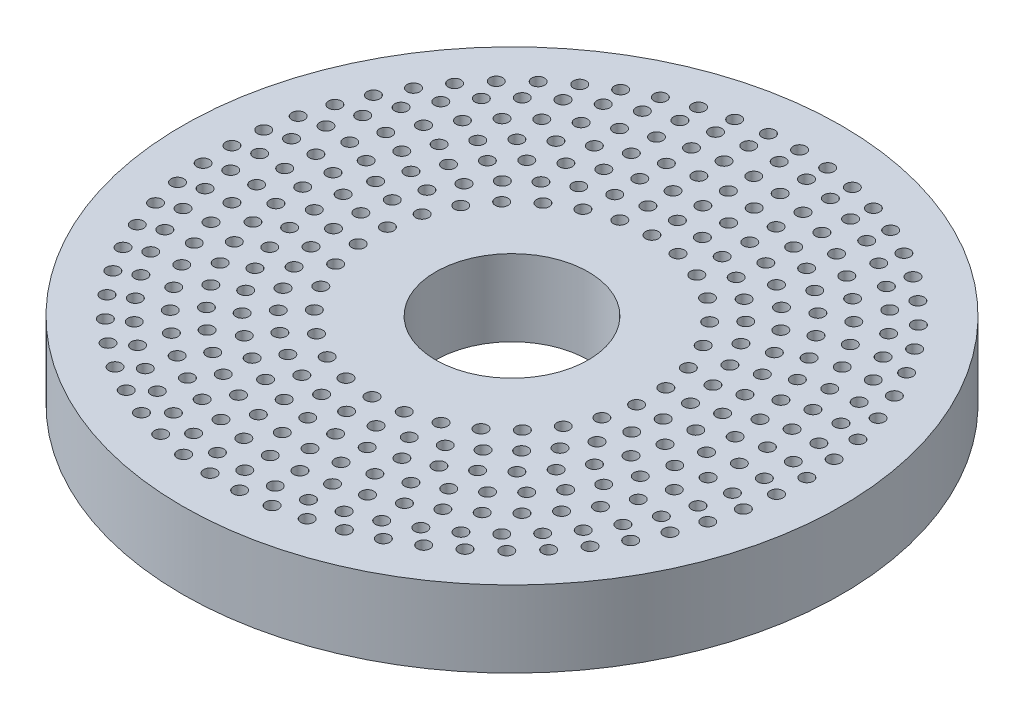
SolidWorks part; units mm, degrees
ref_plane "Ön Düzlem" through (0, 0, 0) normal (0, 0, 1) x (1, 0, 0)
ref_plane "Üst Düzlem" through (0, 0, 0) normal (0, 1, 0) x (1, 0, 0)
ref_plane "Sağ Düzlem" through (0, 0, 0) normal (1, 0, 0) x (0, 0, -1)
sketch "Çizim1" plane through (0, 0, 0) normal (0, 1, 0) x (1, 0, 0)
  line L0 (0, 0) -> (0, 55)
  line L1 (0, 55) -> (0, 65)
  line L2 (0, 65) -> (0, 75)
  line L3 (0, 75) -> (0, 85)
  line L4 (0, 85) -> (0, 95)
  line L5 (0, 95) -> (0, 105)
  line L6 (0, 105) -> (0, 113)
  circle A0 centre (0, 0) radius 129.5
  circle A1 centre (0, 55) radius 2.5
  circle A2 centre (0, 65) radius 2.5
  circle A3 centre (0, 75) radius 2.5
  circle A4 centre (0, 85) radius 2.5
  circle A5 centre (0, 95) radius 2.5
  circle A6 centre (0, 105) radius 2.5
  circle A7 centre (0, 113) radius 2.5
  circle A8 centre (11.4351, 53.7981) radius 2.5
  circle A9 centre (22.3705, 50.245) radius 2.5
  circle A10 centre (32.3282, 44.4959) radius 2.5
  circle A11 centre (40.873, 36.8022) radius 2.5
  circle A12 centre (47.6314, 27.5) radius 2.5
  circle A13 centre (52.3081, 16.9959) radius 2.5
  circle A14 centre (54.6987, 5.7491) radius 2.5
  circle A15 centre (54.6987, -5.7491) radius 2.5
  circle A16 centre (52.3081, -16.9959) radius 2.5
  circle A17 centre (47.6314, -27.5) radius 2.5
  circle A18 centre (40.873, -36.8022) radius 2.5
  circle A19 centre (32.3282, -44.4959) radius 2.5
  circle A20 centre (22.3705, -50.245) radius 2.5
  circle A21 centre (11.4351, -53.7981) radius 2.5
  circle A22 centre (0, -55) radius 2.5
  circle A23 centre (-11.4351, -53.7981) radius 2.5
  circle A24 centre (-22.3705, -50.245) radius 2.5
  circle A25 centre (-32.3282, -44.4959) radius 2.5
  circle A26 centre (-40.873, -36.8022) radius 2.5
  circle A27 centre (-47.6314, -27.5) radius 2.5
  circle A28 centre (-52.3081, -16.9959) radius 2.5
  circle A29 centre (-54.6987, -5.7491) radius 2.5
  circle A30 centre (-54.6987, 5.7491) radius 2.5
  circle A31 centre (-52.3081, 16.9959) radius 2.5
  circle A32 centre (-47.6314, 27.5) radius 2.5
  circle A33 centre (-40.873, 36.8022) radius 2.5
  circle A34 centre (-32.3282, 44.4959) radius 2.5
  circle A35 centre (-22.3705, 50.245) radius 2.5
  circle A36 centre (-11.4351, 53.7981) radius 2.5
  circle A37 centre (10.6986, 64.1135) radius 2.5
  circle A38 centre (21.1055, 61.4781) radius 2.5
  circle A39 centre (30.9366, 57.1658) radius 2.5
  circle A40 centre (39.9238, 51.2941) radius 2.5
  circle A41 centre (47.8221, 44.0233) radius 2.5
  circle A42 centre (54.4158, 35.5516) radius 2.5
  circle A43 centre (59.5253, 26.1102) radius 2.5
  circle A44 centre (63.011, 15.9566) radius 2.5
  circle A45 centre (64.778, 5.3677) radius 2.5
  circle A46 centre (64.778, -5.3677) radius 2.5
  circle A47 centre (63.011, -15.9566) radius 2.5
  circle A48 centre (59.5253, -26.1102) radius 2.5
  circle A49 centre (54.4158, -35.5516) radius 2.5
  circle A50 centre (47.8221, -44.0233) radius 2.5
  circle A51 centre (39.9238, -51.2941) radius 2.5
  circle A52 centre (30.9366, -57.1658) radius 2.5
  circle A53 centre (21.1055, -61.4781) radius 2.5
  circle A54 centre (10.6986, -64.1135) radius 2.5
  circle A55 centre (0, -65) radius 2.5
  circle A56 centre (-10.6986, -64.1135) radius 2.5
  circle A57 centre (-21.1055, -61.4781) radius 2.5
  circle A58 centre (-30.9366, -57.1658) radius 2.5
  circle A59 centre (-39.9238, -51.2941) radius 2.5
  circle A60 centre (-47.8221, -44.0233) radius 2.5
  circle A61 centre (-54.4158, -35.5516) radius 2.5
  circle A62 centre (-59.5253, -26.1102) radius 2.5
  circle A63 centre (-63.011, -15.9566) radius 2.5
  circle A64 centre (-64.778, -5.3677) radius 2.5
  circle A65 centre (-64.778, 5.3677) radius 2.5
  circle A66 centre (-63.011, 15.9566) radius 2.5
  circle A67 centre (-59.5253, 26.1102) radius 2.5
  circle A68 centre (-54.4158, 35.5516) radius 2.5
  circle A69 centre (-47.8221, 44.0233) radius 2.5
  circle A70 centre (-39.9238, 51.2941) radius 2.5
  circle A71 centre (-30.9366, 57.1658) radius 2.5
  circle A72 centre (-21.1055, 61.4781) radius 2.5
  circle A73 centre (-10.6986, 64.1135) radius 2.5
  circle A74 centre (10.9201, 74.2008) radius 2.5
  circle A75 centre (21.6074, 71.82) radius 2.5
  circle A76 centre (31.8343, 67.9086) radius 2.5
  circle A77 centre (41.3826, 62.5498) radius 2.5
  circle A78 centre (50.0489, 55.8579) radius 2.5
  circle A79 centre (57.6485, 47.9755) radius 2.5
  circle A80 centre (64.0195, 39.0705) radius 2.5
  circle A81 centre (69.026, 29.3329) radius 2.5
  circle A82 centre (72.5613, 18.97) radius 2.5
  circle A83 centre (74.5501, 8.2028) radius 2.5
  circle A84 centre (74.95, -2.7392) radius 2.5
  circle A85 centre (73.7524, -13.6228) radius 2.5
  circle A86 centre (70.983, -24.216) radius 2.5
  circle A87 centre (66.7007, -34.2932) radius 2.5
  circle A88 centre (60.9967, -43.6394) radius 2.5
  circle A89 centre (53.9928, -52.0556) radius 2.5
  circle A90 centre (45.838, -59.3622) radius 2.5
  circle A91 centre (36.7063, -65.4037) radius 2.5
  circle A92 centre (26.7923, -70.0512) radius 2.5
  circle A93 centre (16.3073, -73.2057) radius 2.5
  circle A94 centre (5.4746, -74.7999) radius 2.5
  circle A95 centre (-5.4746, -74.7999) radius 2.5
  circle A96 centre (-16.3073, -73.2057) radius 2.5
  circle A97 centre (-26.7923, -70.0512) radius 2.5
  circle A98 centre (-36.7063, -65.4037) radius 2.5
  circle A99 centre (-45.838, -59.3622) radius 2.5
  circle A100 centre (-53.9928, -52.0556) radius 2.5
  circle A101 centre (-60.9967, -43.6394) radius 2.5
  circle A102 centre (-66.7007, -34.2932) radius 2.5
  circle A103 centre (-70.983, -24.216) radius 2.5
  circle A104 centre (-73.7524, -13.6228) radius 2.5
  circle A105 centre (-74.95, -2.7392) radius 2.5
  circle A106 centre (-74.5501, 8.2028) radius 2.5
  circle A107 centre (-72.5613, 18.97) radius 2.5
  circle A108 centre (-69.026, 29.3329) radius 2.5
  circle A109 centre (-64.0195, 39.0705) radius 2.5
  circle A110 centre (-57.6485, 47.9755) radius 2.5
  circle A111 centre (-50.0489, 55.8579) radius 2.5
  circle A112 centre (-41.3826, 62.5498) radius 2.5
  circle A113 centre (-31.8343, 67.9086) radius 2.5
  circle A114 centre (-21.6074, 71.82) radius 2.5
  circle A115 centre (-10.9201, 74.2008) radius 2.5
  circle A116 centre (10.8696, 84.3022) radius 2.5
  circle A117 centre (21.5606, 82.2201) radius 2.5
  circle A118 centre (31.8977, 78.7879) radius 2.5
  circle A119 centre (41.711, 74.0621) radius 2.5
  circle A120 centre (50.8394, 68.1202) radius 2.5
  circle A121 centre (59.133, 61.0597) radius 2.5
  circle A122 centre (66.4557, 52.9966) radius 2.5
  circle A123 centre (72.6871, 44.0634) radius 2.5
  circle A124 centre (77.7251, 34.4066) radius 2.5
  circle A125 centre (81.4868, 24.1848) radius 2.5
  circle A126 centre (83.9105, 13.566) radius 2.5
  circle A127 centre (84.9563, 2.7244) radius 2.5
  circle A128 centre (84.6072, -8.162) radius 2.5
  circle A129 centre (82.8689, -18.9143) radius 2.5
  circle A130 centre (79.7698, -29.356) radius 2.5
  circle A131 centre (75.3609, -39.3158) radius 2.5
  circle A132 centre (69.7146, -48.6299) radius 2.5
  circle A133 centre (62.9236, -57.1456) radius 2.5
  circle A134 centre (55.0994, -64.7229) radius 2.5
  circle A135 centre (46.3705, -71.2375) radius 2.5
  circle A136 centre (36.8801, -76.5824) radius 2.5
  circle A137 centre (26.7842, -80.6697) radius 2.5
  circle A138 centre (16.2485, -83.4325) radius 2.5
  circle A139 centre (5.446, -84.8254) radius 2.5
  circle A140 centre (-5.446, -84.8254) radius 2.5
  circle A141 centre (-16.2485, -83.4325) radius 2.5
  circle A142 centre (-26.7842, -80.6697) radius 2.5
  circle A143 centre (-36.8801, -76.5824) radius 2.5
  circle A144 centre (-46.3705, -71.2375) radius 2.5
  circle A145 centre (-55.0994, -64.7229) radius 2.5
  circle A146 centre (-62.9236, -57.1456) radius 2.5
  circle A147 centre (-69.7146, -48.6299) radius 2.5
  circle A148 centre (-75.3609, -39.3158) radius 2.5
  circle A149 centre (-79.7698, -29.356) radius 2.5
  circle A150 centre (-82.8689, -18.9143) radius 2.5
  circle A151 centre (-84.6072, -8.162) radius 2.5
  circle A152 centre (-84.9563, 2.7244) radius 2.5
  circle A153 centre (-83.9105, 13.566) radius 2.5
  circle A154 centre (-81.4868, 24.1848) radius 2.5
  circle A155 centre (-77.7251, 34.4066) radius 2.5
  circle A156 centre (-72.6871, 44.0634) radius 2.5
  circle A157 centre (-66.4557, 52.9966) radius 2.5
  circle A158 centre (-59.133, 61.0597) radius 2.5
  circle A159 centre (-50.8394, 68.1202) radius 2.5
  circle A160 centre (-41.711, 74.0621) radius 2.5
  circle A161 centre (-31.8977, 78.7879) radius 2.5
  circle A162 centre (-21.5606, 82.2201) radius 2.5
  circle A163 centre (-10.8696, 84.3022) radius 2.5
  circle A164 centre (11.0288, 94.3576) radius 2.5
  circle A165 centre (21.9085, 92.4393) radius 2.5
  circle A166 centre (32.4919, 89.2708) radius 2.5
  circle A167 centre (42.6359, 84.8951) radius 2.5
  circle A168 centre (52.2034, 79.3713) radius 2.5
  circle A169 centre (61.0648, 72.7742) radius 2.5
  circle A170 centre (69.1005, 65.193) radius 2.5
  circle A171 centre (76.2017, 56.7301) radius 2.5
  circle A172 centre (82.2724, 47.5) radius 2.5
  circle A173 centre (87.2305, 37.6276) radius 2.5
  circle A174 centre (91.009, 27.2463) radius 2.5
  circle A175 centre (93.5567, 16.4966) radius 2.5
  circle A176 centre (94.8393, 5.5238) radius 2.5
  circle A177 centre (94.8393, -5.5238) radius 2.5
  circle A178 centre (93.5567, -16.4966) radius 2.5
  circle A179 centre (91.009, -27.2463) radius 2.5
  circle A180 centre (87.2305, -37.6276) radius 2.5
  circle A181 centre (82.2724, -47.5) radius 2.5
  circle A182 centre (76.2017, -56.7301) radius 2.5
  circle A183 centre (69.1005, -65.193) radius 2.5
  circle A184 centre (61.0648, -72.7742) radius 2.5
  circle A185 centre (52.2034, -79.3713) radius 2.5
  circle A186 centre (42.6359, -84.8951) radius 2.5
  circle A187 centre (32.4919, -89.2708) radius 2.5
  circle A188 centre (21.9085, -92.4393) radius 2.5
  circle A189 centre (11.0288, -94.3576) radius 2.5
  circle A190 centre (0, -95) radius 2.5
  circle A191 centre (-11.0288, -94.3576) radius 2.5
  circle A192 centre (-21.9085, -92.4393) radius 2.5
  circle A193 centre (-32.4919, -89.2708) radius 2.5
  circle A194 centre (-42.6359, -84.8951) radius 2.5
  circle A195 centre (-52.2034, -79.3713) radius 2.5
  circle A196 centre (-61.0648, -72.7742) radius 2.5
  circle A197 centre (-69.1005, -65.193) radius 2.5
  circle A198 centre (-76.2017, -56.7301) radius 2.5
  circle A199 centre (-82.2724, -47.5) radius 2.5
  circle A200 centre (-87.2305, -37.6276) radius 2.5
  circle A201 centre (-91.009, -27.2463) radius 2.5
  circle A202 centre (-93.5567, -16.4966) radius 2.5
  circle A203 centre (-94.8393, -5.5238) radius 2.5
  circle A204 centre (-94.8393, 5.5238) radius 2.5
  circle A205 centre (-93.5567, 16.4966) radius 2.5
  circle A206 centre (-91.009, 27.2463) radius 2.5
  circle A207 centre (-87.2305, 37.6276) radius 2.5
  circle A208 centre (-82.2724, 47.5) radius 2.5
  circle A209 centre (-76.2017, 56.7301) radius 2.5
  circle A210 centre (-69.1005, 65.193) radius 2.5
  circle A211 centre (-61.0648, 72.7742) radius 2.5
  circle A212 centre (-52.2034, 79.3713) radius 2.5
  circle A213 centre (-42.6359, 84.8951) radius 2.5
  circle A214 centre (-32.4919, 89.2708) radius 2.5
  circle A215 centre (-21.9085, 92.4393) radius 2.5
  circle A216 centre (-11.0288, 94.3576) radius 2.5
  circle A217 centre (11.3525, 104.3845) radius 2.5
  circle A218 centre (22.5719, 102.5452) radius 2.5
  circle A219 centre (33.5267, 99.5036) radius 2.5
  circle A220 centre (44.0884, 95.2954) radius 2.5
  circle A221 centre (54.1332, 89.97) radius 2.5
  circle A222 centre (63.5433, 83.5898) radius 2.5
  circle A223 centre (72.2084, 76.2295) radius 2.5
  circle A224 centre (80.027, 67.9756) radius 2.5
  circle A225 centre (86.9073, 58.9246) radius 2.5
  circle A226 centre (92.7688, 49.1829) radius 2.5
  circle A227 centre (97.5426, 38.8645) radius 2.5
  circle A228 centre (101.1727, 28.0905) radius 2.5
  circle A229 centre (103.6168, 16.9871) radius 2.5
  circle A230 centre (104.846, 5.6846) radius 2.5
  circle A231 centre (104.846, -5.6846) radius 2.5
  circle A232 centre (103.6168, -16.9871) radius 2.5
  circle A233 centre (101.1727, -28.0905) radius 2.5
  circle A234 centre (97.5426, -38.8645) radius 2.5
  circle A235 centre (92.7688, -49.1829) radius 2.5
  circle A236 centre (86.9073, -58.9246) radius 2.5
  circle A237 centre (80.027, -67.9756) radius 2.5
  circle A238 centre (72.2084, -76.2295) radius 2.5
  circle A239 centre (63.5433, -83.5898) radius 2.5
  circle A240 centre (54.1332, -89.97) radius 2.5
  circle A241 centre (44.0884, -95.2954) radius 2.5
  circle A242 centre (33.5267, -99.5036) radius 2.5
  circle A243 centre (22.5719, -102.5452) radius 2.5
  circle A244 centre (11.3525, -104.3845) radius 2.5
  circle A245 centre (0, -105) radius 2.5
  circle A246 centre (-11.3525, -104.3845) radius 2.5
  circle A247 centre (-22.5719, -102.5452) radius 2.5
  circle A248 centre (-33.5267, -99.5036) radius 2.5
  circle A249 centre (-44.0884, -95.2954) radius 2.5
  circle A250 centre (-54.1332, -89.97) radius 2.5
  circle A251 centre (-63.5433, -83.5898) radius 2.5
  circle A252 centre (-72.2084, -76.2295) radius 2.5
  circle A253 centre (-80.027, -67.9756) radius 2.5
  circle A254 centre (-86.9073, -58.9246) radius 2.5
  circle A255 centre (-92.7688, -49.1829) radius 2.5
  circle A256 centre (-97.5426, -38.8645) radius 2.5
  circle A257 centre (-101.1727, -28.0905) radius 2.5
  circle A258 centre (-103.6168, -16.9871) radius 2.5
  circle A259 centre (-104.846, -5.6846) radius 2.5
  circle A260 centre (-104.846, 5.6846) radius 2.5
  circle A261 centre (-103.6168, 16.9871) radius 2.5
  circle A262 centre (-101.1727, 28.0905) radius 2.5
  circle A263 centre (-97.5426, 38.8645) radius 2.5
  circle A264 centre (-92.7688, 49.1829) radius 2.5
  circle A265 centre (-86.9073, 58.9246) radius 2.5
  circle A266 centre (-80.027, 67.9756) radius 2.5
  circle A267 centre (-72.2084, 76.2295) radius 2.5
  circle A268 centre (-63.5433, 83.5898) radius 2.5
  circle A269 centre (-54.1332, 89.97) radius 2.5
  circle A270 centre (-44.0884, 95.2954) radius 2.5
  circle A271 centre (-33.5267, 99.5036) radius 2.5
  circle A272 centre (-22.5719, 102.5452) radius 2.5
  circle A273 centre (-11.3525, 104.3845) radius 2.5
  circle A274 centre (11.6188, 112.4011) radius 2.5
  circle A275 centre (23.1144, 110.6107) radius 2.5
  circle A276 centre (34.365, 107.6478) radius 2.5
  circle A277 centre (45.2513, 103.5438) radius 2.5
  circle A278 centre (55.6579, 98.3422) radius 2.5
  circle A279 centre (65.4746, 92.0982) radius 2.5
  circle A280 centre (74.5972, 84.8779) radius 2.5
  circle A281 centre (82.929, 76.7579) radius 2.5
  circle A282 centre (90.3818, 67.8242) radius 2.5
  circle A283 centre (96.8766, 58.1716) radius 2.5
  circle A284 centre (102.3444, 47.9023) radius 2.5
  circle A285 centre (106.7273, 37.1253) radius 2.5
  circle A286 centre (109.9789, 25.9547) radius 2.5
  circle A287 centre (112.0647, 14.509) radius 2.5
  circle A288 centre (112.9625, 2.9095) radius 2.5
  circle A289 centre (112.663, -8.7208) radius 2.5
  circle A290 centre (111.1692, -20.2587) radius 2.5
  circle A291 centre (108.4969, -31.5819) radius 2.5
  circle A292 centre (104.6746, -42.5703) radius 2.5
  circle A293 centre (99.7427, -53.1074) radius 2.5
  circle A294 centre (93.7535, -63.0815) radius 2.5
  circle A295 centre (86.7705, -72.387) radius 2.5
  circle A296 centre (78.8677, -80.9252) radius 2.5
  circle A297 centre (70.1289, -88.6055) radius 2.5
  circle A298 centre (60.6467, -95.3466) radius 2.5
  circle A299 centre (50.5216, -101.077) radius 2.5
  circle A300 centre (39.861, -105.736) radius 2.5
  circle A301 centre (28.7778, -109.2741) radius 2.5
  circle A302 centre (17.3896, -111.6539) radius 2.5
  circle A303 centre (5.8171, -112.8502) radius 2.5
  circle A304 centre (-5.8171, -112.8502) radius 2.5
  circle A305 centre (-17.3896, -111.6539) radius 2.5
  circle A306 centre (-28.7778, -109.2741) radius 2.5
  circle A307 centre (-39.861, -105.736) radius 2.5
  circle A308 centre (-50.5216, -101.077) radius 2.5
  circle A309 centre (-60.6467, -95.3466) radius 2.5
  circle A310 centre (-70.1289, -88.6055) radius 2.5
  circle A311 centre (-78.8677, -80.9252) radius 2.5
  circle A312 centre (-86.7705, -72.387) radius 2.5
  circle A313 centre (-93.7535, -63.0815) radius 2.5
  circle A314 centre (-99.7427, -53.1074) radius 2.5
  circle A315 centre (-104.6746, -42.5703) radius 2.5
  circle A316 centre (-108.4969, -31.5819) radius 2.5
  circle A317 centre (-111.1692, -20.2587) radius 2.5
  circle A318 centre (-112.663, -8.7208) radius 2.5
  circle A319 centre (-112.9625, 2.9095) radius 2.5
  circle A320 centre (-112.0647, 14.509) radius 2.5
  circle A321 centre (-109.9789, 25.9547) radius 2.5
  circle A322 centre (-106.7273, 37.1253) radius 2.5
  circle A323 centre (-102.3444, 47.9023) radius 2.5
  circle A324 centre (-96.8766, 58.1716) radius 2.5
  circle A325 centre (-90.3818, 67.8242) radius 2.5
  circle A326 centre (-82.929, 76.7579) radius 2.5
  circle A327 centre (-74.5972, 84.8779) radius 2.5
  circle A328 centre (-65.4746, 92.0982) radius 2.5
  circle A329 centre (-55.6579, 98.3422) radius 2.5
  circle A330 centre (-45.2513, 103.5438) radius 2.5
  circle A331 centre (-34.365, 107.6478) radius 2.5
  circle A332 centre (-23.1144, 110.6107) radius 2.5
  circle A333 centre (-11.6188, 112.4011) radius 2.5
  point P77 (0, 0)
  point P152 (0, 0)
  point P237 (0, 0)
  point P334 (0, 0)
  point P441 (0, 0)
  point P556 (0, 0)
  point P677 (0, 0)
  dimension "D1" = 259
  dimension "D2" = 30
  dimension "D3" = 38
  dimension "D4" = 43
  dimension "D5" = 49
  dimension "D6" = 54
  dimension "D7" = 58
  dimension "D8" = 61
extrude "Yükseklik-Ekstrüzyon2" add sketch "Çizim1" along normal blind 30 contours A0 A333 A332 A331 A330 A329 A328 A327 A326 A325 A324 A323 A322 A321 A320 A319 A318 A317 A316 A315 A314 A313 A312 A311 A310 A309
sketch "Çizim2" plane through (0, 30, 0) normal (0, 1, 0) x (1, 0, 0)
  circle A0 centre (0, 0) radius 30
extrude "Kes-Ekstrüzyon1" cut sketch "Çizim2" against normal blind 30
